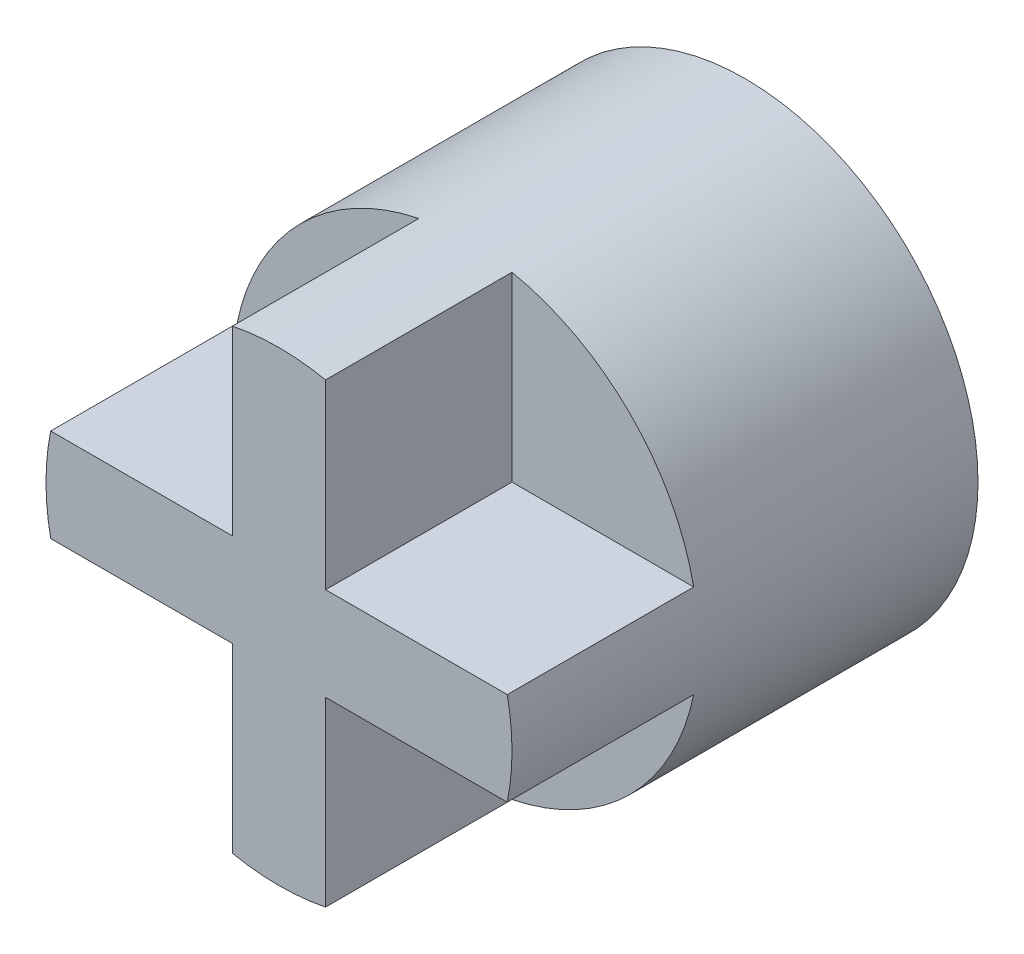
SolidWorks part; units mm, degrees
ref_plane "Front Plane" through (0, 0, 0) normal (0, 0, 1) x (1, 0, 0)
ref_plane "Top Plane" through (0, 0, 0) normal (0, 1, 0) x (1, 0, 0)
ref_plane "Right Plane" through (0, 0, 0) normal (1, 0, 0) x (0, 0, -1)
sketch "Sketch1" plane through (0, 0, 0) normal (0, 0, 1) x (1, 0, 0)
  circle A0 centre (0, 0) radius 6.35
  dimension "D1" = 12.7
extrude "Boss-Extrude1" add sketch "Sketch1" along normal blind 7.62
sketch "Sketch2" plane through (0, 0, 7.62) normal (0, 0, 1) x (1, 0, 0)
  line L1 (1.27, -6.5744) -> (-1.27, -6.5744)
  line L2 (1.27, -6.5744) -> (1.27, 6.5744)
  line L3 (1.27, 6.5744) -> (-1.27, 6.5744)
  line L4 (-1.27, -6.5744) -> (-1.27, 6.5744)
  line L5 (1.27, -6.5744) -> (-1.27, 6.5744) construction
  line L6 (1.27, 6.5744) -> (-1.27, -6.5744) construction
  line L7 (-6.685, 1.27) -> (6.685, 1.27)
  line L8 (-6.685, 1.27) -> (-6.685, -1.27)
  line L9 (-6.685, -1.27) -> (6.685, -1.27)
  line L10 (6.685, 1.27) -> (6.685, -1.27)
  line L11 (-6.685, 1.27) -> (6.685, -1.27) construction
  line L12 (-6.685, -1.27) -> (6.685, 1.27) construction
  point P0 (0, 0)
  point P6 (0, 0)
  circle M9 centre (0, 0) radius 6.35
  dimension "D1" = 2.54
extrude "Boss-Extrude2" add sketch "Sketch2" along normal blind 5.08 contours L4 L7 L2 M9 | L9 L4 L7 M9 | L4 L9 L2 L7 | L2 L9 L7 M9 | L9 L4 L2 M9
sketch "Sketch3" plane through (0, 0, 0) normal (0, 0, -1) x (-1, 0, 0)
  circle A0 centre (0, 0) radius 3.048
  dimension "D1" = 6.096
extrude "Cut-Extrude1" cut sketch "Sketch3" against normal blind 3.81
